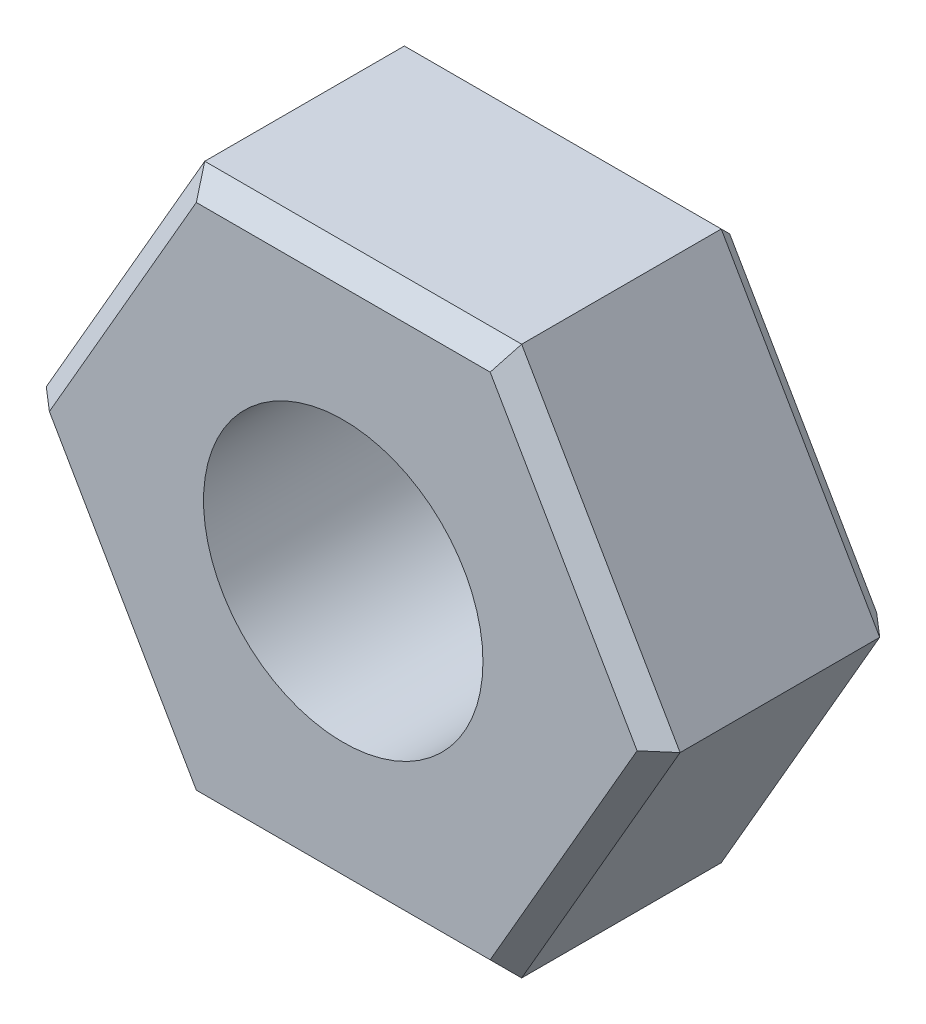
SolidWorks part; units mm, degrees
ref_plane "Front Plane" through (0, 0, 0) normal (0, 0, 1) x (1, 0, 0)
ref_plane "Top Plane" through (0, 0, 0) normal (0, 1, 0) x (1, 0, 0)
ref_plane "Right Plane" through (0, 0, 0) normal (1, 0, 0) x (0, 0, -1)
sketch "Nut Hex Sketch" plane through (0, 0, 0) normal (0, 0, 1) x (1, 0, 0)
  line L1 (3.1754, 0) -> (1.5877, 2.75)
  line L2 (1.5877, 2.75) -> (-1.5877, 2.75)
  line L3 (-1.5877, 2.75) -> (-3.1754, 0)
  line L4 (-3.1754, 0) -> (-1.5877, -2.75)
  line L5 (-1.5877, -2.75) -> (1.5877, -2.75)
  line L6 (1.5877, -2.75) -> (3.1754, 0)
  circle A0 centre (0, 0) radius 2.75 construction
  dimension "D1" = 5.5
extrude "Nut Hex Extrude" add sketch "Nut Hex Sketch" along normal blind 2.4
chamfer "Hex Edge Chamfers" distance 0.2 12 edges at (2.3816, -1.375, 0) (2.3816, 1.375, 0) (0, 2.75, 0) (-2.3816, 1.375, 0) (-2.3816, -1.375, 0) (0, -2.75, 0) (2.3816, -1.375, 2.4) (2.3816, 1.375, 2.4) (0, 2.75, 2.4) (-2.3816, 1.375, 2.4) (-2.3816, -1.375, 2.4) (0, -2.75, 2.4)
sketch "Thread Bore Sketch" plane through (0, 0, 0) normal (0, 0, 1) x (1, 0, 0)
  circle A0 centre (0, 0) radius 1.4
  dimension "D1" = 2.8
extrude "Thread Bore Cut" cut sketch "Thread Bore Sketch" along normal through all
equation "\"nut_across_flats\"= 5.5mm 'M3 nut hex across flats"
equation "\"nut_height\"= 2.4mm 'Metal hex height"
equation "\"thread_bore_diameter\"= 2.8mm 'Simplified thread bore"
equation "\"edge_break\"= 0.2mm 'Native edge break on hex perimeter"
equation "\"D1@Nut Hex Sketch\"= \"nut_across_flats\""
equation "\"D1@Nut Hex Extrude\"= \"nut_height\""
equation "\"D1@Hex Edge Chamfers\"= \"edge_break\""
equation "\"D1@Thread Bore Sketch\"= \"thread_bore_diameter\""
